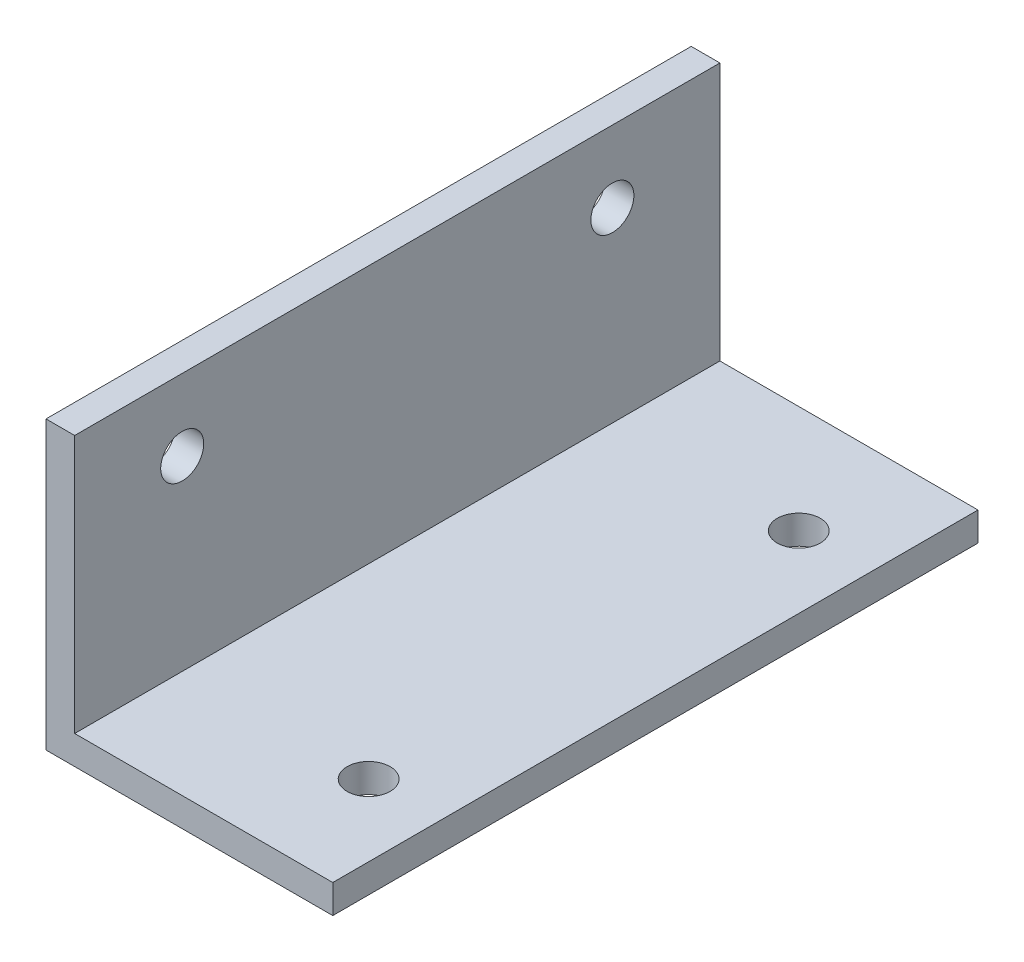
SolidWorks part; units mm, degrees
material "6061 合金"
ref_plane "前视基准面" through (0, 0, 0) normal (0, 0, 1) x (1, 0, 0)
ref_plane "上视基准面" through (0, 0, 0) normal (0, 1, 0) x (1, 0, 0)
ref_plane "右视基准面" through (0, 0, 0) normal (1, 0, 0) x (0, 0, -1)
sketch "草图1" plane through (0, 0, 0) normal (0, 0, 1) x (1, 0, 0)
  line L0 (0, 0) -> (0, 18)
  line L1 (0, 18) -> (-2, 18)
  line L2 (-2, 18) -> (-2, -2)
  line L3 (-2, -2) -> (18, -2)
  line L4 (18, -2) -> (18, 0)
  line L5 (18, 0) -> (0, 0)
  dimension "D1" = 2
  dimension "D2" = 20
extrude "凸台-拉伸1" add sketch "草图1" along normal blind 45
sketch "草图2" plane through (0, 0, 0) normal (1, 0, 0) x (0, 0, -1)
  line L0 (-22.5, 18) -> (-22.5, 0) construction
  line L1 (-45, 18) -> (0, 18) construction
  line L2 (-45, 0) -> (0, 0) construction
  line L3 (-45, 13) -> (0, 13) construction
  line L4 (-45, 0) -> (-45, 18) construction
  line L5 (0, 0) -> (0, 18) construction
  circle A0 centre (-37.5, 13) radius 1.5
  circle A1 centre (-7.5, 13) radius 1.5
  dimension "D2" = 15
  dimension "D3" = 3
  dimension "D1" = 13
extrude "切除-拉伸1" cut sketch "草图2" against normal through all
sketch "草图3" plane through (0, 0, 0) normal (0, 1, 0) x (1, 0, 0)
  line L0 (13, 0) -> (13, -45) construction
  line L1 (18, 0) -> (0, 0) construction
  line L2 (18, -45) -> (0, -45) construction
  line L3 (0, -45) -> (0, 0) construction
  line L4 (0, -22.5) -> (18, -22.5) construction
  line L5 (18, -45) -> (18, 0) construction
  circle A0 centre (13, -37.5) radius 1.5
  circle A1 centre (13, -7.5) radius 1.5
  dimension "D2" = 15
  dimension "D3" = 3
  dimension "D1" = 13
extrude "切除-拉伸2" cut sketch "草图3" against normal through all
